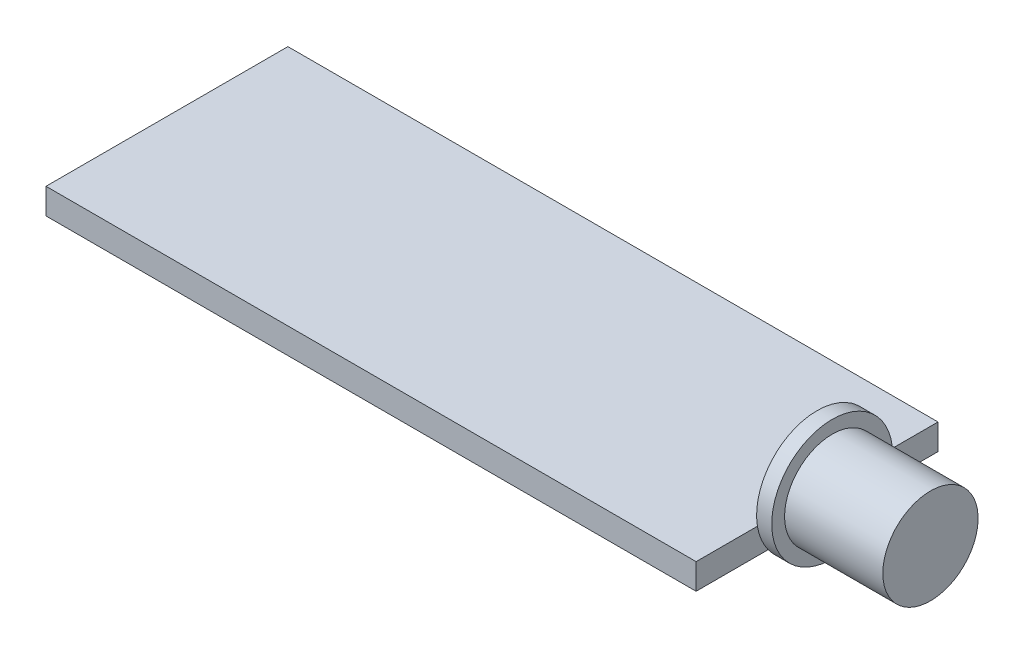
SolidWorks part; units mm, degrees
ref_plane "Front Plane" through (0, 0, 0) normal (0, 0, 1) x (1, 0, 0)
ref_plane "Top Plane" through (0, 0, 0) normal (0, 1, 0) x (1, 0, 0)
ref_plane "Right Plane" through (0, 0, 0) normal (1, 0, 0) x (0, 0, -1)
sketch "Sketch1" plane through (0, 0, 0) normal (0, 1, 0) x (1, 0, 0)
  line L1 (0, 0) -> (43, 0)
  line L2 (0, 0) -> (0, 16)
  line L3 (0, 16) -> (43, 16)
  line L4 (43, 0) -> (43, 16)
  dimension "D1" = 16
  dimension "D2" = 43
extrude "Boss-Extrude1" add sketch "Sketch1" along normal blind 1.7
sketch "Sketch2" plane through (43, 0, 0) normal (1, 0, 0) x (0, 0, -1)
  line L0 (0, 1.7) -> (16, 1.7) construction
  line L1 (0, 1.7) -> (0, 0) construction
  circle A0 centre (8, 2.35) radius 4
  dimension "D1" = 8
  dimension "D2" = 0.65
  dimension "D3" = 8
extrude "Boss-Extrude2" add sketch "Sketch2" along normal blind 1
sketch "Sketch3" plane through (44, 0, 0) normal (1, 0, 0) x (0, 0, -1)
  circle A0 centre (8, 2.35) radius 3.15
  circle A1 centre (8, 2.35) radius 4 construction
  dimension "D1" = 6.3
extrude "Boss-Extrude3" add sketch "Sketch3" along normal blind 6.5
